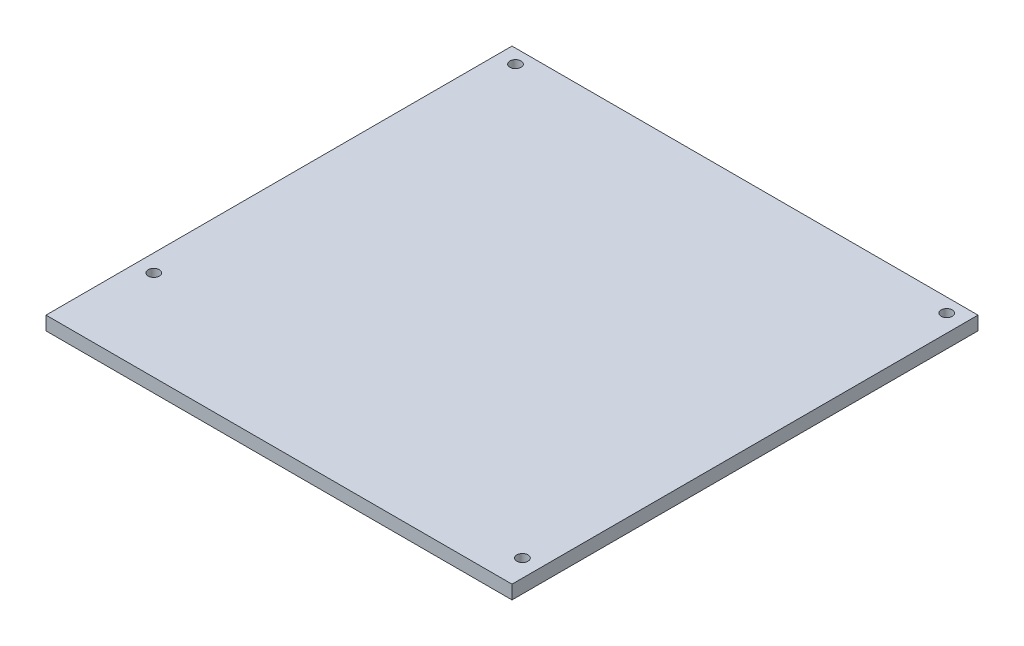
SolidWorks part; units mm, degrees
ref_plane "Front Plane" through (0, 0, 0) normal (0, 0, 1) x (1, 0, 0)
ref_plane "Top Plane" through (0, 0, 0) normal (0, 1, 0) x (1, 0, 0)
ref_plane "Right Plane" through (0, 0, 0) normal (1, 0, 0) x (0, 0, -1)
sketch "Sketch1" plane through (0, 0, 0) normal (0, 1, 0) x (1, 0, 0)
  line L1 (-85.09, -85.09) -> (85.09, -85.09)
  line L2 (-85.09, -85.09) -> (-85.09, 85.09)
  line L3 (-85.09, 85.09) -> (85.09, 85.09)
  line L4 (85.09, -85.09) -> (85.09, 85.09)
  line L5 (-85.09, -85.09) -> (85.09, 85.09) construction
  line L6 (-85.09, 85.09) -> (85.09, -85.09) construction
  point P0 (0, 0)
  dimension "D1" = 170.18
  dimension "D2" = 170.18
extrude "Boss-Extrude1" add sketch "Sketch1" along normal blind 5
hole_wizard "0.16 (1) Diameter Hole1" positions "Sketch3" profile "Sketch2" hole size "1" standard "Ansi Inch" end condition through all
sketch "Sketch3" plane through (0, 5, 0) normal (0, 1, 0) x (-1, 0, 0)
  line L2 (85.09, 85.09) -> (-85.09, 85.09) construction
  line L3 (-85.09, 85.09) -> (-85.09, -85.09) construction
  point P0 (78.74, -80.01)
  point P1 (-78.74, -80.01)
  point P3 (-78.74, 74.93)
  point P5 (78.74, 52.07)
  dimension "D1" = 10.16
  dimension "D2" = 6.35
  dimension "D3" = 157.48
  dimension "D4" = 22.86
  dimension "D5" = 154.94
sketch "Sketch2" plane through (-78.74, 5, -80.01) normal (1, 0, 0) x (0, 0, 1)
  line L0 (0, 0) -> (0, 5)
  line L1 (0, 5) -> (2.032, 5)
  line L2 (2.032, 5) -> (2.032, 0)
  line L5 (2.032, 0) -> (0, 0)
  line L11 (0, -6.35) -> (0, 107.95) construction
  dimension "Thru Hole Dia." = 4.064
  dimension "Thru Hole Depth" = 5
